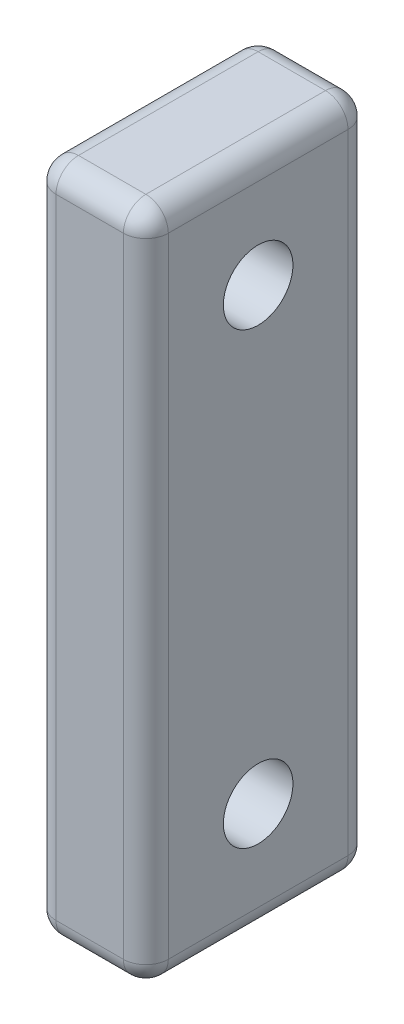
SolidWorks part; units mm, degrees
material "PET"
ref_plane "Front Plane" through (0, 0, 0) normal (0, 0, 1) x (1, 0, 0)
ref_plane "Top Plane" through (0, 0, 0) normal (0, 1, 0) x (1, 0, 0)
ref_plane "Right Plane" through (0, 0, 0) normal (1, 0, 0) x (0, 0, -1)
sketch "Sketch1" plane through (0, 0, 0) normal (0, 0, 1) x (1, 0, 0)
  line L1 (-6.35, 38.1) -> (6.35, 38.1)
  line L2 (-6.35, 38.1) -> (-6.35, -38.1)
  line L3 (-6.35, -38.1) -> (6.35, -38.1)
  line L4 (6.35, 38.1) -> (6.35, -38.1)
  line L5 (-6.35, 38.1) -> (6.35, -38.1) construction
  line L6 (-6.35, -38.1) -> (6.35, 38.1) construction
  point P0 (0, 0)
  dimension "D1" = 12.7
  dimension "D2" = 76.2
extrude "Boss-Extrude1" add sketch "Sketch1" along normal blind 25.4
hole_wizard "#97 (0.31) Diameter Hole1" positions "Sketch2" profile "Sketch3" hole size "#97" standard "ANSI Inch" end condition through all
sketch "Sketch2" plane through (6.35, 0, 0) normal (1, 0, 0) x (0, 0, -1)
  line L0 (-25.4, 38.1) -> (0, 38.1) construction
  line L1 (-25.4, -38.1) -> (0, -38.1) construction
  point P0 (-12.7, 25.4)
  point P2 (-12.7, -25.4)
  dimension "D1" = 12.7
  dimension "D2" = 12.7
sketch "Sketch3" plane through (6.35, 25.4, 12.7) normal (0, 1, 0) x (0, 0, -1)
  line L0 (0, 0) -> (0, 12.7)
  line L1 (0, 12.7) -> (3.937, 12.7)
  line L2 (3.937, 12.7) -> (3.937, 0)
  line L5 (3.937, 0) -> (0, 0)
  line L11 (0, -6.35) -> (0, 107.95) construction
  dimension "Thru Hole Dia." = 7.874
  dimension "Thru Hole Depth" = 12.7
fillet "Fillet1" radius 2.54 12 edges at (0, 38.1, 0) (-6.35, 38.1, 12.7) (0, 38.1, 25.4) (-6.35, 0, 25.4) (-6.35, 0, 0) (0, -38.1, 0) (0, -38.1, 25.4) (6.35, -38.1, 12.7) (-6.35, -38.1, 12.7) (6.35, 0, 0) (6.35, 38.1, 12.7) (6.35, 0, 25.4)
